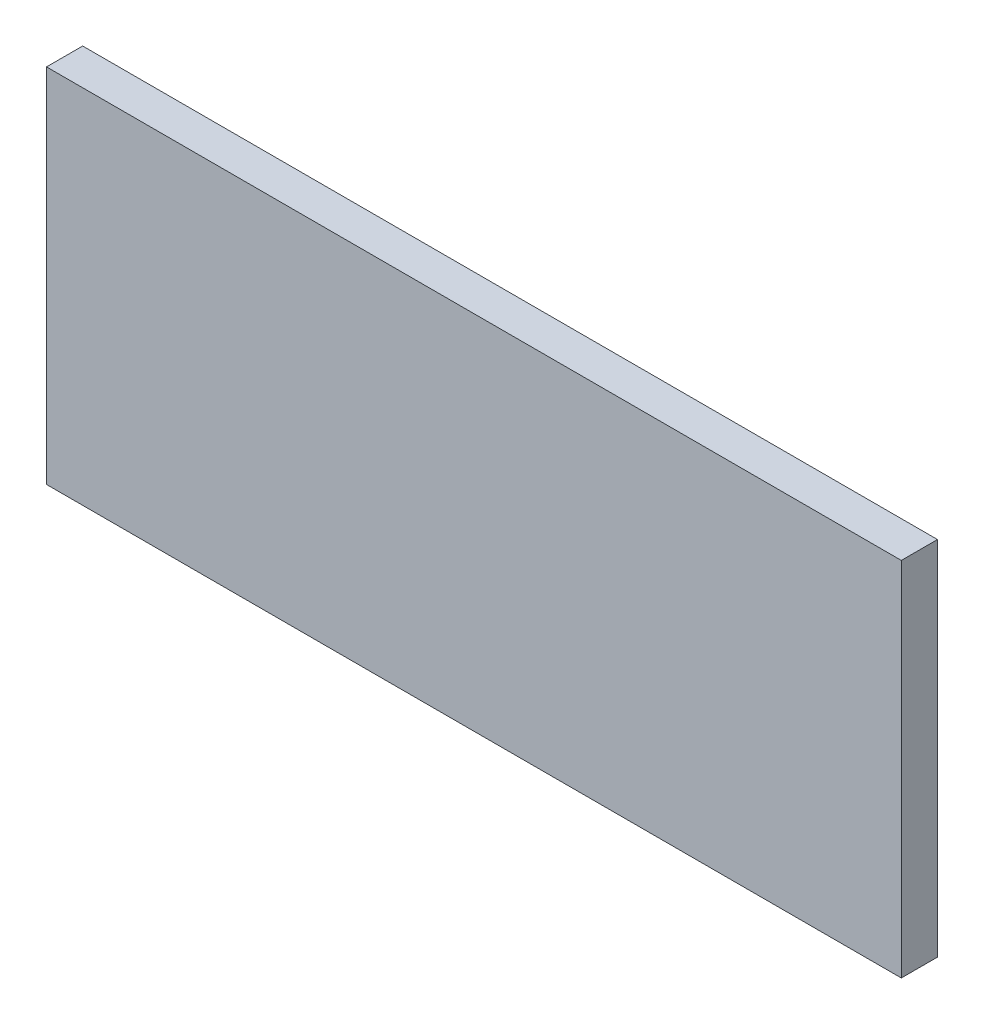
SolidWorks part; units mm, degrees
material "1.0721 (10S20)"
ref_plane "Alzado" through (0, 0, 0) normal (0, 0, 1) x (1, 0, 0)
ref_plane "Planta" through (0, 0, 0) normal (0, 1, 0) x (1, 0, 0)
ref_plane "Vista lateral" through (0, 0, 0) normal (1, 0, 0) x (0, 0, -1)
sketch "Croquis1" plane through (0, 0, 0) normal (0, 0, 1) x (1, 0, 0)
  line L1 (-26, -11) -> (26, -11)
  line L2 (-26, -11) -> (-26, 11)
  line L3 (-26, 11) -> (26, 11)
  line L4 (26, -11) -> (26, 11)
  line L5 (-26, -11) -> (26, 11) construction
  line L6 (-26, 11) -> (26, -11) construction
  point P0 (0, 0)
  dimension "D1" = 52
  dimension "D2" = 22
extrude "Saliente-Extruir1" add sketch "Croquis1" along normal mid plane 2.2
